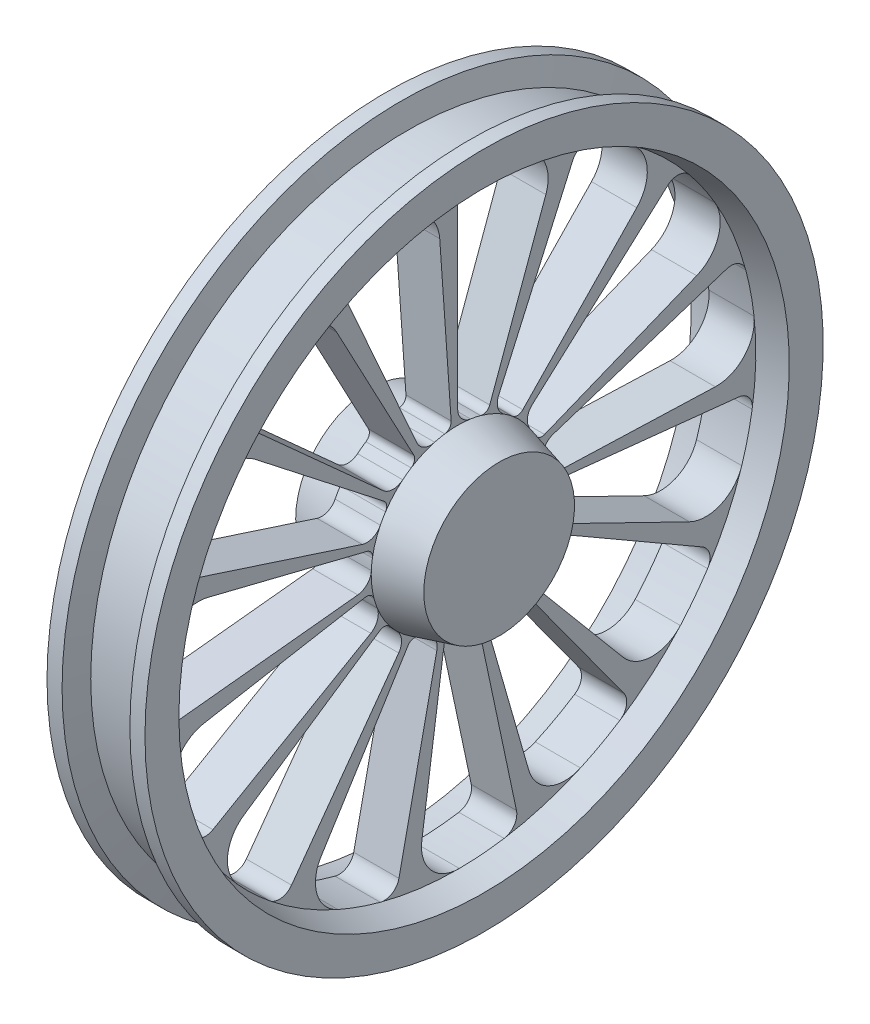
SolidWorks part; units mm, degrees
material "Alliage 1060"
ref_plane "Plan de face" through (0, 0, 0) normal (0, 0, 1) x (1, 0, 0)
ref_plane "Plan de dessus" through (0, 0, 0) normal (0, 1, 0) x (1, 0, 0)
ref_plane "Plan de droite" through (0, 0, 0) normal (1, 0, 0) x (0, 0, -1)
sketch "Esquisse1" plane through (0, 0, 0) normal (0, 0, 1) x (1, 0, 0)
  line L0 (-448.1556, 0) -> (448.1556, 0) construction
  line L1 (0, 0) -> (0, 494.0053) construction
  line L2 (-85, 0) -> (-85, 100)
  line L3 (-85, 100) -> (-30, 114.7372)
  line L4 (-30, 114.7372) -> (-30, 395.6218)
  line L5 (-30, 395.6218) -> (-65, 405)
  line L6 (-65, 405) -> (-65, 450)
  line L7 (-65, 450) -> (-45, 450)
  line L8 (-45, 450) -> (-36.9615, 420)
  line L9 (-36.9615, 420) -> (36.9615, 420)
  line L10 (-85, 100) -> (-220.664, 100) construction
  line L11 (45, 450) -> (36.9615, 420)
  line L12 (65, 450) -> (45, 450)
  line L13 (65, 405) -> (65, 450)
  line L14 (30, 395.6218) -> (65, 405)
  line L15 (30, 114.7372) -> (30, 395.6218)
  line L16 (85, 100) -> (30, 114.7372)
  line L17 (85, 0) -> (85, 100)
  line L18 (-65, 405) -> (-175.0973, 405) construction
  line L19 (-45, 450) -> (-45, 478.3489) construction
  line L20 (-85, 0) -> (85, 0)
  point P16 (0, 420)
  point P24 (-30, 420)
  dimension "D1" = 900
  dimension "D2" = 200
  dimension "D3" = 15
  dimension "D4" = 60
  dimension "D5" = 170
  dimension "D6" = 130
  dimension "D7" = 30
  dimension "D8" = 45
  dimension "D9" = 15
  dimension "D10" = 15
  dimension "D11" = 20
revolve "Révolution1" add sketch "Esquisse1" angle 360 about L0
sketch "Esquisse2" plane through (30, 0, 0) normal (1, 0, 0) x (0, 0, -1)
  line L0 (0, 0) -> (0, 529.0066) construction
  line L1 (0, 0) -> (184.1774, 506.0234) construction
  line L2 (0, 375.0889) -> (0, 133.2446)
  line L3 (42.5253, 116.8374) -> (116.9661, 321.3617)
  line L4 (152.5624, 342.6608) -> (54.1954, 121.725)
  line L5 (86.3708, 89.4396) -> (237.5634, 246.0041)
  line L6 (278.7454, 250.9835) -> (99.02, 89.158)
  line L7 (115.2821, 46.577) -> (317.0839, 128.1102)
  line L8 (356.7308, 115.9089) -> (126.7231, 41.1748)
  line L9 (124.26, -4.3393) -> (341.7777, -11.9351)
  line L10 (373.0342, -39.2075) -> (132.5146, -13.9278)
  line L11 (111.7522, -54.5052) -> (307.375, -149.9168)
  line L12 (324.8366, -187.5445) -> (115.3932, -66.6223)
  line L13 (79.9215, -95.2467) -> (219.8244, -261.9765)
  line L14 (220.4718, -303.4533) -> (78.3192, -107.7971)
  line L15 (34.2716, -119.5192) -> (94.2641, -328.738)
  line L16 (77.9854, -366.8924) -> (27.7031, -130.3329)
  line L17 (-17.3042, -123.1257) -> (-47.5952, -338.6578)
  line L18 (-77.9854, -366.8924) -> (-27.7031, -130.3329)
  line L19 (-65.8879, -105.4427) -> (-181.225, -290.0206)
  line L20 (-220.4718, -303.4533) -> (-78.3192, -107.7971)
  line L21 (-103.079, -69.5277) -> (-283.5192, -191.2361)
  line L22 (-324.8366, -187.5445) -> (-115.3932, -66.6223)
  line L23 (-122.4468, -21.5907) -> (-336.7904, -59.3852)
  line L24 (-373.0342, -39.2075) -> (-132.5146, -13.9278)
  line L25 (-120.6424, 30.0795) -> (-331.8275, 82.7339)
  line L26 (-356.7308, 115.9089) -> (-126.7231, 41.1748)
  line L27 (-97.9779, 76.5487) -> (-269.4886, 210.5476)
  line L28 (-278.7454, 250.9835) -> (-99.02, 89.158)
  line L29 (-58.3721, 109.7819) -> (-160.5527, 301.9557)
  line L30 (-152.5624, 342.6608) -> (-54.1954, 121.725)
  line L31 (-8.6732, 124.0328) -> (-23.8557, 341.1529)
  circle A0 centre (0, 0) radius 395.6218 construction
  arc A1 (80.1055, 387.427) -> (21.0649, 395.0606) centre (0, 0) ccw
  circle A2 centre (0, 0) radius 114.7372 construction
  arc A3 (30.4725, 110.6167) -> (17.0313, 113.4661) centre (0, 0) ccw
  arc A4 (42.5253, 116.8374) -> (30.4725, 110.6167) centre (33.1284, 120.2576) cw
  arc A5 (0, 375.0889) -> (21.0649, 395.0606) centre (20, 375.0889) cw
  arc A6 (0, 133.2446) -> (17.0313, 113.4661) centre (20, 133.2446) ccw
  arc A7 (116.9661, 321.3617) -> (80.1055, 387.427) centre (69.9815, 338.4627) ccw
  arc A8 (230.7608, 321.3504) -> (179.9294, 352.3379) centre (0, 0) ccw
  arc A9 (237.5634, 246.0041) -> (230.7608, 321.3504) centre (201.5964, 280.737) ccw
  arc A10 (152.5624, 342.6608) -> (179.9294, 352.3379) centre (170.8333, 334.5261) cw
  arc A11 (54.1954, 121.725) -> (61.7097, 96.7292) centre (72.4664, 113.5902) ccw
  arc A12 (72.8299, 88.6591) -> (61.7097, 96.7292) centre (0, 0) ccw
  arc A13 (86.3708, 89.4396) -> (72.8299, 88.6591) centre (79.1774, 96.3862) cw
  arc A14 (341.5154, 199.7093) -> (307.6824, 248.6929) centre (0, 0) ccw
  arc A15 (317.0839, 128.1102) -> (341.5154, 199.7093) centre (298.3536, 174.4694) ccw
  arc A16 (278.7454, 250.9835) -> (307.6824, 248.6929) centre (292.128, 236.1206) cw
  arc A17 (99.02, 89.158) -> (95.7179, 63.267) centre (112.4026, 74.2951) ccw
  arc A18 (102.5943, 51.3715) -> (95.7179, 63.267) centre (0, 0) ccw
  arc A19 (115.2821, 46.577) -> (102.5943, 51.3715) centre (111.536, 55.8488) cw
  arc A20 (393.219, 43.5367) -> (382.2344, 102.0465) centre (0, 0) ccw
  arc A21 (341.7777, -11.9351) -> (393.219, 43.5367) centre (343.5226, 38.0344) ccw
  arc A22 (356.7308, 115.9089) -> (382.2344, 102.0465) centre (362.9111, 96.8877) cw
  arc A23 (126.7231, 41.1748) -> (113.1757, 18.8653) centre (132.9035, 22.1537) ccw
  arc A24 (114.6193, 5.2013) -> (113.1757, 18.8653) centre (0, 0) ccw
  arc A25 (124.26, -4.3393) -> (114.6193, 5.2013) centre (124.609, 5.6547) cw
  arc A26 (376.9314, -120.1638) -> (390.6945, -62.2446) centre (0, 0) ccw
  arc A27 (307.375, -149.9168) -> (376.9314, -120.1638) centre (329.2935, -104.9771) ccw
  arc A28 (373.0342, -39.2075) -> (390.6945, -62.2446) centre (370.9436, -59.0979) cw
  arc A29 (132.5146, -13.9278) -> (111.0643, -28.7984) centre (130.4241, -33.8183) ccw
  arc A30 (106.8255, -41.8682) -> (111.0643, -28.7984) centre (0, 0) ccw
  arc A31 (111.7522, -54.5052) -> (106.8255, -41.8682) centre (116.1359, -45.5173) cw
  arc A32 (295.4689, -263.0869) -> (331.6, -215.773) centre (0, 0) ccw
  arc A33 (219.8244, -261.9765) -> (295.4689, -263.0869) centre (258.1266, -229.8371) ccw
  arc A34 (324.8366, -187.5445) -> (331.6, -215.773) centre (314.8366, -204.865) cw
  arc A35 (115.3932, -66.6223) -> (89.7489, -71.4826) centre (105.3932, -83.9428) ccw
  arc A36 (80.5606, -81.6983) -> (89.7489, -71.4826) centre (0, 0) ccw
  arc A37 (79.9215, -95.2467) -> (80.5606, -81.6983) centre (87.5819, -88.8188) cw
  arc A38 (162.9172, -360.5199) -> (215.1689, -331.9924) centre (0, 0) ccw
  arc A39 (94.2641, -328.738) -> (162.9172, -360.5199) centre (142.3272, -314.9562) ccw
  arc A40 (220.4718, -303.4533) -> (215.1689, -331.9924) centre (204.2914, -315.209) cw
  arc A41 (78.3192, -107.7971) -> (52.9151, -101.8067) centre (62.1389, -119.5528) ccw
  arc A42 (40.3661, -107.4021) -> (52.9151, -101.8067) centre (0, 0) ccw
  arc A43 (34.2716, -119.5192) -> (40.3661, -107.4021) centre (43.8842, -116.7628) cw
  arc A44 (2.1956, -395.6157) -> (61.5331, -390.8072) centre (0, 0) ccw
  arc A45 (-47.5952, -338.6578) -> (2.1956, -395.6157) centre (1.9182, -345.6165) ccw
  arc A46 (77.9854, -366.8924) -> (61.5331, -390.8072) centre (58.4224, -371.0506) cw
  arc A47 (27.7031, -130.3329) -> (6.9319, -114.5276) centre (8.1402, -134.4911) ccw
  arc A48 (-6.8081, -114.535) -> (6.9319, -114.5276) centre (0, 0) ccw
  arc A49 (-17.3042, -123.1257) -> (-6.8081, -114.535) centre (-7.4015, -124.5174) cw
  arc A50 (-158.9056, -362.306) -> (-102.7423, -382.0479) centre (0, 0) ccw
  arc A51 (-181.225, -290.0206) -> (-158.9056, -362.306) centre (-138.8226, -316.5165) ccw
  arc A52 (-77.9854, -366.8924) -> (-102.7423, -382.0479) centre (-97.5483, -362.7341) cw
  arc A53 (-27.7031, -130.3329) -> (-40.25, -107.4456) centre (-47.2661, -126.1746) ccw
  arc A54 (-52.8051, -101.8638) -> (-40.25, -107.4456) centre (0, 0) ccw
  arc A55 (-65.8879, -105.4427) -> (-52.8051, -101.8638) centre (-57.4074, -110.7419) cw
  arc A56 (-292.5306, -266.3502) -> (-249.2526, -307.2291) centre (0, 0) ccw
  arc A57 (-283.5192, -191.2361) -> (-292.5306, -266.3502) centre (-255.5596, -232.688) ccw
  arc A58 (-220.4718, -303.4533) -> (-249.2526, -307.2291) centre (-236.6521, -291.6976) cw
  arc A59 (-78.3192, -107.7971) -> (-80.4723, -81.7853) centre (-94.4995, -96.0414) ccw
  arc A60 (-89.6717, -71.5795) -> (-80.4723, -81.7853) centre (0, 0) ccw
  arc A61 (-103.079, -69.5277) -> (-89.6717, -71.5795) centre (-97.4871, -77.818) cw
  arc A62 (-375.5744, -124.3402) -> (-352.6649, -179.2876) centre (0, 0) ccw
  arc A63 (-336.7904, -59.3852) -> (-375.5744, -124.3402) centre (-328.108, -108.6256) ccw
  arc A64 (-324.8366, -187.5445) -> (-352.6649, -179.2876) centre (-334.8366, -170.224) cw
  arc A65 (-115.3932, -66.6223) -> (-106.7802, -41.9836) centre (-125.3932, -49.3018) ccw
  arc A66 (-111.0331, -28.9183) -> (-106.7802, -41.9836) centre (0, 0) ccw
  arc A67 (-122.4468, -21.5907) -> (-111.0331, -28.9183) centre (-120.7103, -31.4387) cw
  arc A68 (-393.678, 39.1695) -> (-395.0983, -20.3456) centre (0, 0) ccw
  arc A69 (-331.8275, 82.7339) -> (-393.678, 39.1695) centre (-343.9236, 34.2191) ccw
  arc A70 (-373.0342, -39.2075) -> (-395.0983, -20.3456) centre (-375.1247, -19.317) cw
  arc A71 (-132.5146, -13.9278) -> (-114.6248, 5.0775) centre (-134.6052, 5.9626) ccw
  arc A72 (-113.196, 18.743) -> (-114.6248, 5.0775) centre (0, 0) ccw
  arc A73 (-120.6424, 30.0795) -> (-113.196, 18.743) centre (-123.0616, 20.3766) cw
  arc A74 (-343.7111, 195.9064) -> (-369.2155, 142.1143) centre (0, 0) ccw
  arc A75 (-269.4886, 210.5476) -> (-343.7111, 195.9064) centre (-300.2717, 171.1471) ccw
  arc A76 (-356.7308, 115.9089) -> (-369.2155, 142.1143) centre (-350.5505, 134.93) cw
  arc A77 (-126.7231, 41.1748) -> (-102.6498, 51.2607) centre (-120.5428, 60.196) ccw
  arc A78 (-95.7862, 63.1635) -> (-102.6498, 51.2607) centre (0, 0) ccw
  arc A79 (-97.9779, 76.5487) -> (-95.7862, 63.1635) centre (-104.1345, 68.6686) cw
  arc A80 (-234.3134, 318.7692) -> (-279.4921, 280.0014) centre (0, 0) ccw
  arc A81 (-160.5527, 301.9557) -> (-234.3134, 318.7692) centre (-204.7001, 278.4821) ccw
  arc A82 (-278.7454, 250.9835) -> (-279.4921, 280.0014) centre (-265.3628, 265.8464) cw
  arc A83 (-99.02, 89.158) -> (-72.9256, 88.5804) centre (-85.6374, 104.0209) ccw
  arc A84 (-61.8141, 96.6625) -> (-72.9256, 88.5804) centre (0, 0) ccw
  arc A85 (-58.3721, 109.7819) -> (-61.8141, 96.6625) centre (-67.2016, 105.0872) cw
  arc A86 (-84.4008, 386.514) -> (-141.4419, 369.4737) centre (0, 0) ccw
  arc A87 (-23.8557, 341.1529) -> (-84.4008, 386.514) centre (-73.7339, 337.6651) ccw
  arc A88 (-152.5624, 342.6608) -> (-141.4419, 369.4737) centre (-134.2915, 350.7955) cw
  arc A89 (-54.1954, 121.725) -> (-30.592, 110.5837) centre (-35.9245, 129.8597) ccw
  arc A90 (-17.1538, 113.4477) -> (-30.592, 110.5837) centre (0, 0) ccw
  arc A91 (-8.6732, 124.0328) -> (-17.1538, 113.4477) centre (-18.6489, 123.3353) cw
  point P14 (39.2424, 107.8177)
  point P17 (0, 395.6218)
  point P20 (0, 114.7372)
  point P23 (135.3106, 371.7629)
  point P195 (0, 0)
  dimension "D2" = 10
  dimension "D3" = 20
  dimension "D4" = 50
  dimension "D1" = 20
  dimension "D5" = 15
extrude "Enlèv. mat.-Extru.1" cut sketch "Esquisse2" against normal up to next
equation "\"A\"= 130"
equation "\"B\"= 900"
equation "\"D1@Esquisse1\"=\"B\""
equation "\"D6@Esquisse1\"=\"A\""
